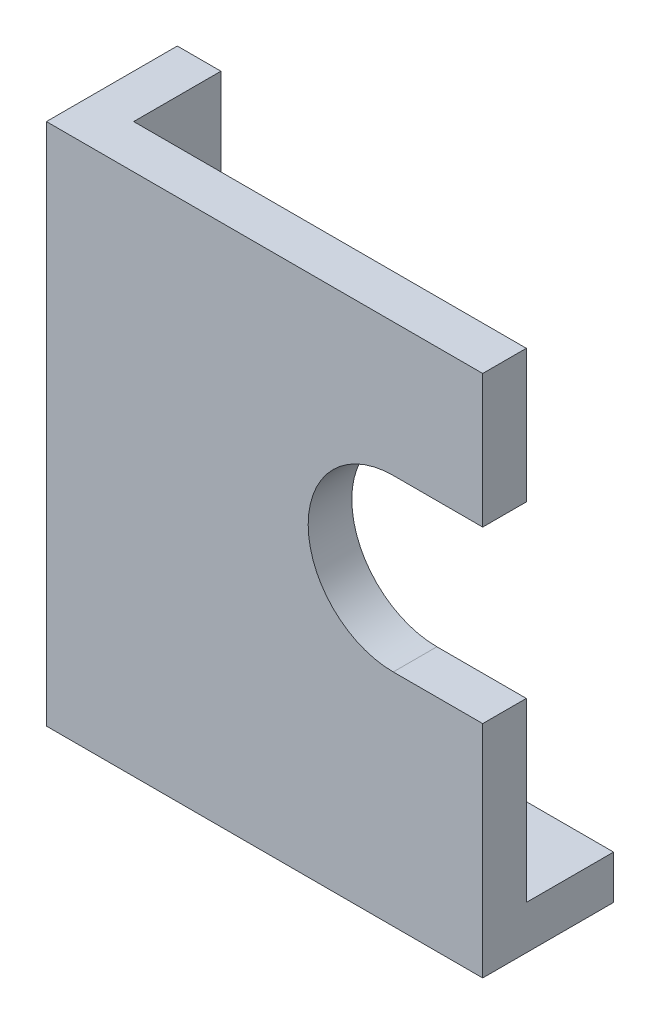
SolidWorks part; units mm, degrees
ref_plane "Front Plane" through (0, 0, 0) normal (0, 0, 1) x (1, 0, 0)
ref_plane "Top Plane" through (0, 0, 0) normal (0, 1, 0) x (1, 0, 0)
ref_plane "Right Plane" through (0, 0, 0) normal (1, 0, 0) x (0, 0, -1)
sketch "Sketch1" plane through (0, 0, 0) normal (1, 0, 0) x (0, 0, -1)
  line L0 (0, -10) -> (0, 90)
  line L1 (0, 90) -> (10, 90)
  line L2 (10, 90) -> (10, 0)
  line L3 (10, 0) -> (25, 0)
  line L4 (25, 0) -> (25, -10)
  line L5 (25, -10) -> (0, -10)
  dimension "D1" = 10
  dimension "D2" = 10
  dimension "D3" = 100
  dimension "D4" = 15
extrude "Boss-Extrude1" add sketch "Sketch1" along normal blind 60
sketch "Sketch4" plane through (0, 0, 0) normal (-1, 0, 0) x (0, 0, 1)
  line L1 (0, 90) -> (-10, 90)
  line L2 (0, 90) -> (0, 0)
  line L3 (0, 0) -> (-10, 0)
  line L4 (-10, 90) -> (-10, 0)
extrude "Boss-Extrude2" add sketch "Sketch4" along normal blind 45
sketch "Sketch6" plane through (0, 0, 0) normal (-1, 0, 0) x (0, 0, 1)
  line L0 (-25, -10) -> (-25, 0) construction
  line L1 (0, 0) -> (-25, 0)
  line L2 (0, 0) -> (0, -10)
  line L3 (0, -10) -> (-25, -10)
  line L4 (-25, 0) -> (-25, -10)
  line L5 (0, -10) -> (-25, -10) construction
extrude "Boss-Extrude3" add sketch "Sketch6" along normal blind 45
sketch "Sketch8" plane through (0, 0, 0) normal (0, 1, 0) x (1, 0, 0)
  line L0 (60, 10) -> (-45, 10) construction
  line L1 (-45, 25) -> (-35, 25)
  line L2 (-45, 25) -> (-45, 10)
  line L3 (-45, 10) -> (-35, 10)
  line L4 (-35, 25) -> (-35, 10)
  dimension "D1" = 10
extrude "Boss-Extrude4" add sketch "Sketch8" along normal blind 90
sketch "Sketch9" plane through (0, 0, -10) normal (0, 0, -1) x (-1, 0, 0)
  line L0 (35, 90) -> (35, 0) construction
  line L1 (-60, 0) -> (35, 0) construction
  line L2 (-34.5, 40.5) -> (-60, 40.5)
  line L3 (-60, 0) -> (-60, 90) construction
  line L4 (-34.5, 79.5) -> (-60, 79.5)
  line L5 (-60, 40.5) -> (-60, 79.5)
  arc A0 (-34.5, 40.5) -> (-34.5, 79.5) centre (-34.5, 60) ccw
  dimension "D1" = 39
  dimension "D2" = 69.5
  dimension "D3" = 60
extrude "Cut-Extrude1" cut sketch "Sketch9" against normal blind 10
sketch "Sketch10" plane through (0, 90, 0) normal (0, 1, 0) x (1, 0, 0)
  line L6 (60, 10) -> (-35, 10)
  line L7 (-35, 10) -> (-35, 25)
  line L8 (-35, 25) -> (-45, 25)
  line L9 (-45, 25) -> (-45, 0)
  line L10 (-45, 0) -> (60, 0)
  line L11 (60, 0) -> (60, 10)
  line L12 (60, 10) -> (-35, 10)
  line L13 (-35, 10) -> (-35, 25)
  line L14 (-35, 25) -> (-45, 25)
  line L15 (-45, 25) -> (-45, 0)
  line L16 (-45, 0) -> (60, 0)
  line L17 (60, 0) -> (60, 10)
  dimension "D1" = 0
extrude "Boss-Extrude5" add sketch "Sketch10" along normal blind 20
sketch "Sketch11" plane through (60, 0, 0) normal (1, 0, 0) x (0, 0, -1)
  line L6 (10, 0) -> (10, 40.5)
  line L7 (10, 40.5) -> (0, 40.5)
  line L8 (0, 40.5) -> (0, -10)
  line L9 (0, -10) -> (25, -10)
  line L10 (25, -10) -> (25, 0)
  line L11 (25, 0) -> (10, 0)
  line L12 (10, 0) -> (10, 40.5)
  line L13 (10, 40.5) -> (0, 40.5)
  line L14 (0, 40.5) -> (0, -10)
  line L15 (0, -10) -> (25, -10)
  line L16 (25, -10) -> (25, 0)
  line L17 (25, 0) -> (10, 0)
  dimension "D1" = 0
extrude "Cut-Extrude2" cut sketch "Sketch11" against normal blind 5
sketch "Sketch12" plane through (60, 0, 0) normal (1, 0, 0) x (0, 0, -1)
  line L4 (0, 110) -> (0, 79.5)
  line L5 (0, 79.5) -> (10, 79.5)
  line L6 (10, 79.5) -> (10, 110)
  line L7 (10, 110) -> (0, 110)
  line L8 (0, 110) -> (0, 79.5)
  line L9 (0, 79.5) -> (10, 79.5)
  line L10 (10, 79.5) -> (10, 110)
  line L11 (10, 110) -> (0, 110)
  dimension "D1" = 0
extrude "Cut-Extrude3" cut sketch "Sketch12" against normal blind 5
sketch "Sketch13" plane through (0, 0, -25) normal (0, 0, -1) x (-1, 0, 0)
  line L6 (35, 0) -> (-55, 0)
  line L7 (-55, 0) -> (-55, -10)
  line L8 (-55, -10) -> (45, -10)
  line L9 (45, -10) -> (45, 110)
  line L10 (45, 110) -> (35, 110)
  line L11 (35, 110) -> (35, 0)
  line L12 (35, 0) -> (-55, 0)
  line L13 (-55, 0) -> (-55, -10)
  line L14 (-55, -10) -> (45, -10)
  line L15 (45, -10) -> (45, 110)
  line L16 (45, 110) -> (35, 110)
  line L17 (35, 110) -> (35, 0)
  dimension "D1" = 0
extrude "Boss-Extrude6" add sketch "Sketch13" along normal blind 5
